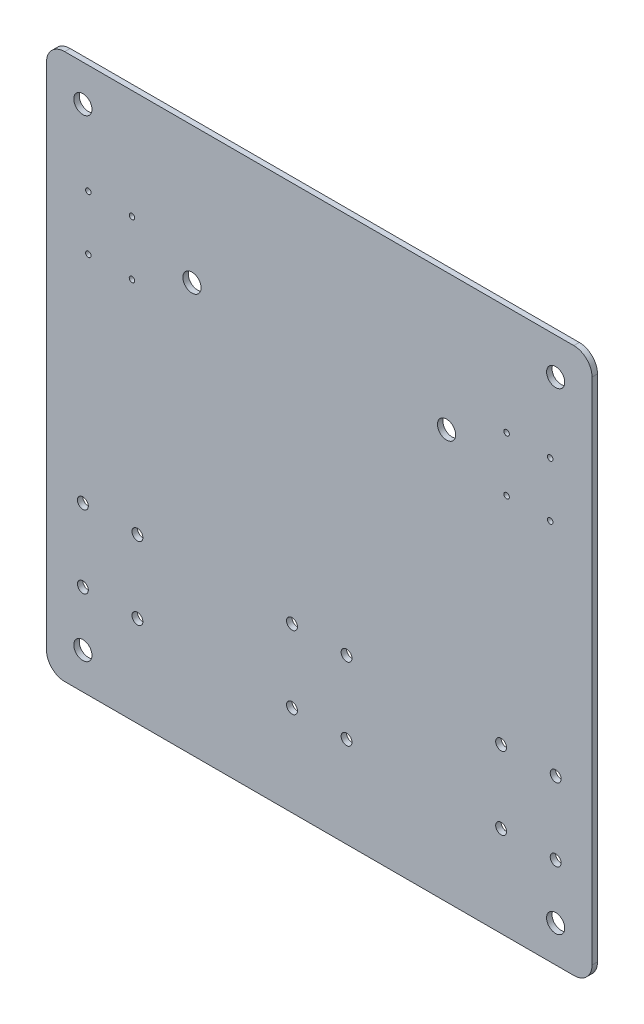
SolidWorks part; units mm, degrees
ref_plane "前视基准面" through (0, 0, 0) normal (0, 0, 1) x (1, 0, 0)
ref_plane "上视基准面" through (0, 0, 0) normal (0, 1, 0) x (1, 0, 0)
ref_plane "右视基准面" through (0, 0, 0) normal (1, 0, 0) x (0, 0, -1)
sketch "草图1" plane through (0, 0, 0) normal (0, 0, 1) x (1, 0, 0)
  line L1 (-150, 150) -> (150, 150)
  line L2 (-150, 150) -> (-150, -150)
  line L3 (-150, -150) -> (150, -150)
  line L4 (150, 150) -> (150, -150)
  dimension "D1" = 300
  dimension "D2" = 300
  dimension "D3" = 150
  dimension "D4" = 150
extrude "凸台-拉伸1" add sketch "草图1" along normal blind 3
sketch "草图2" plane through (0, 0, 3) normal (0, 0, 1) x (1, 0, 0)
  line L0 (150, -150) -> (150, 150) construction
  line L1 (150, 150) -> (-150, 150) construction
  circle A0 centre (103, 90) radius 1.5
  circle A1 centre (127, 90) radius 1.5
  circle A2 centre (103, 60) radius 1.5
  circle A3 centre (127, 60) radius 1.5
  dimension "D1" = 3
  dimension "D2" = 3
  dimension "D3" = 3
  dimension "D4" = 3
  dimension "D5" = 30
  dimension "D6" = 30
  dimension "D7" = 23
  dimension "D8" = 24
  dimension "D9" = 60
  dimension "D10" = 60
  dimension "D11" = 24
  dimension "D12" = 23
extrude "切除-拉伸1" cut sketch "草图2" against normal through all
mirror "镜向1" about plane through (0, 0, 0) normal (1, 0, 0) of "切除-拉伸1"
fillet "圆角1" radius 10 4 edges at (-150, -150, 1.5) (150, -150, 1.5) (150, 150, 1.5) (-150, 150, 1.5)
sketch "草图3" plane through (0, 0, 3) normal (0, 0, 1) x (1, 0, 0)
  line L0 (140, 150) -> (-140, 150) construction
  line L1 (-150, 140) -> (-150, -140) construction
  circle A0 centre (-130, 130) radius 5
  dimension "D1" = 10
  dimension "D3" = 20
  dimension "D2" = 20
extrude "切除-拉伸2" cut sketch "草图3" against normal through all
mirror "镜向2" about plane through (0, 0, 0) normal (1, 0, 0) of "切除-拉伸2"
mirror "镜向3" about plane through (0, 0, 0) normal (0, 1, 0) of "镜向2", "切除-拉伸2"
sketch "草图4" plane through (0, 0, 3) normal (0, 0, 1) x (1, 0, 0)
  line L0 (140, 150) -> (-140, 150) construction
  line L1 (150, -140) -> (150, 140) construction
  line L2 (-150, 140) -> (-150, -140) construction
  circle A0 centre (-70, 75) radius 5
  circle A1 centre (70, 75) radius 5
  dimension "D1" = 10
  dimension "D2" = 10
  dimension "D3" = 75
  dimension "D4" = 80
  dimension "D5" = 75
  dimension "D6" = 80
extrude "切除-拉伸3" cut sketch "草图4" against normal through all
sketch "草图5" plane through (0, 0, 3) normal (0, 0, 1) x (1, 0, 0)
  line L0 (-130, -130) -> (-130, -20.8214) construction
  line L1 (-140, -150) -> (140, -150) construction
  line L2 (-130, -60) -> (-78.7549, -60) construction
  line L3 (-130, -100) -> (-75.0583, -100) construction
  circle A0 centre (-130, -100) radius 3
  circle A1 centre (-130, -60) radius 3
  circle A2 centre (-100, -60) radius 3
  circle A3 centre (-100, -100) radius 3
  dimension "D1" = 6
  dimension "D2" = 6
  dimension "D3" = 40
  dimension "D4" = 50
  dimension "D5" = 6
  dimension "D6" = 6
  dimension "D7" = 30
  dimension "D8" = 30
extrude "切除-拉伸4" cut sketch "草图5" against normal through all
mirror "镜向4" about plane through (0, 0, 0) normal (1, 0, 0) of "切除-拉伸4"
sketch "草图6" plane through (0, 0, 3) normal (0, 0, 1) x (1, 0, 0)
  line L0 (0, 0) -> (0, -163.5724) construction
  line L1 (-130, -60) -> (130, -60) construction
  line L2 (-130, -100) -> (130, -100) construction
  circle A0 centre (-15, -60) radius 3
  circle A1 centre (15, -60) radius 3
  circle A2 centre (-15, -100) radius 3
  circle A3 centre (15, -100) radius 3
  dimension "D1" = 6
  dimension "D2" = 6
  dimension "D3" = 6
  dimension "D4" = 6
  dimension "D5" = 15
  dimension "D6" = 15
  dimension "D7" = 15
  dimension "D8" = 15
extrude "切除-拉伸5" cut sketch "草图6" against normal through all
